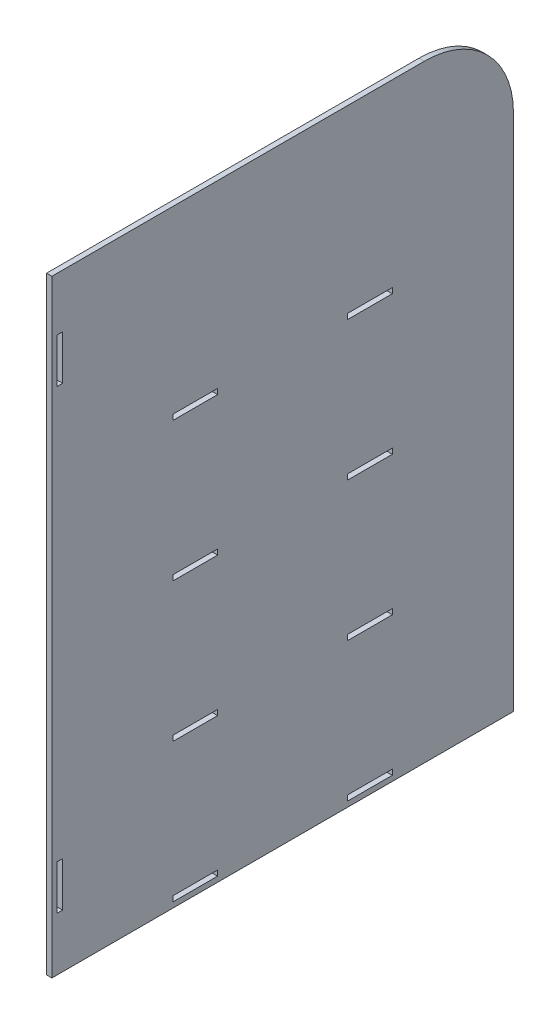
SolidWorks part; units mm, degrees
material "Maple"
ref_plane "Front Plane" through (0, 0, 0) normal (0, 0, 1) x (1, 0, 0)
ref_plane "Top Plane" through (0, 0, 0) normal (0, 1, 0) x (1, 0, 0)
ref_plane "Right Plane" through (0, 0, 0) normal (1, 0, 0) x (0, 0, -1)
sketch "Sketch1" plane through (0, 0, 0) normal (1, 0, 0) x (0, 0, -1)
  line L0 (-155.8318, 16.1512) -> (-414.8318, 16.1512) construction
  line L1 (-414.8318, 357.1512) -> (3.1682, 357.1512)
  line L2 (-414.8318, 357.1512) -> (-414.8318, -324.8488)
  line L3 (-414.8318, -324.8488) -> (103.1682, -324.8488)
  line L4 (103.1682, 257.1512) -> (103.1682, -324.8488)
  line L5 (-414.8318, 357.1512) -> (103.1682, -324.8488) construction
  line L6 (-414.8318, -324.8488) -> (103.1682, 357.1512) construction
  line L7 (-408.8318, 297.1512) -> (-402.8318, 297.1512)
  line L8 (-408.8318, 297.1512) -> (-408.8318, 247.1512)
  line L9 (-408.8318, 247.1512) -> (-402.8318, 247.1512)
  line L10 (-402.8318, 297.1512) -> (-402.8318, 247.1512)
  line L15 (-155.8318, 16.1512) -> (-155.8318, -324.8488) construction
  line L16 (-278.8318, -312.8488) -> (-228.8318, -312.8488)
  line L17 (-278.8318, -312.8488) -> (-278.8318, -318.8488)
  line L18 (-278.8318, -318.8488) -> (-228.8318, -318.8488)
  line L19 (-228.8318, -312.8488) -> (-228.8318, -318.8488)
  line L20 (-278.8318, -312.8488) -> (-228.8318, -318.8488) construction
  line L21 (-278.8318, -318.8488) -> (-228.8318, -312.8488) construction
  line L22 (-32.8318, -318.8488) -> (-82.8318, -318.8488)
  line L23 (-82.8318, -312.8488) -> (-82.8318, -318.8488)
  line L24 (-32.8318, -312.8488) -> (-82.8318, -312.8488)
  line L25 (-32.8318, -312.8488) -> (-32.8318, -318.8488)
  line L26 (-278.8318, -156.8488) -> (-278.8318, -162.8488)
  line L27 (-278.8318, -156.8488) -> (-228.8318, -156.8488)
  line L28 (-228.8318, -156.8488) -> (-228.8318, -162.8488)
  line L29 (-278.8318, -162.8488) -> (-228.8318, -162.8488)
  line L30 (-32.8318, -162.8488) -> (-82.8318, -162.8488)
  line L31 (-82.8318, -156.8488) -> (-82.8318, -162.8488)
  line L32 (-32.8318, -156.8488) -> (-82.8318, -156.8488)
  line L33 (-32.8318, -156.8488) -> (-32.8318, -162.8488)
  line L34 (-278.8318, -0.8488) -> (-278.8318, -6.8488)
  line L35 (-278.8318, -0.8488) -> (-228.8318, -0.8488)
  line L36 (-228.8318, -0.8488) -> (-228.8318, -6.8488)
  line L37 (-278.8318, -6.8488) -> (-228.8318, -6.8488)
  line L38 (-32.8318, -6.8488) -> (-82.8318, -6.8488)
  line L39 (-82.8318, -0.8488) -> (-82.8318, -6.8488)
  line L40 (-32.8318, -0.8488) -> (-82.8318, -0.8488)
  line L41 (-32.8318, -0.8488) -> (-32.8318, -6.8488)
  line L42 (-278.8318, 155.1512) -> (-278.8318, 149.1512)
  line L43 (-278.8318, 155.1512) -> (-228.8318, 155.1512)
  line L44 (-228.8318, 155.1512) -> (-228.8318, 149.1512)
  line L45 (-278.8318, 149.1512) -> (-228.8318, 149.1512)
  line L46 (-32.8318, 149.1512) -> (-82.8318, 149.1512)
  line L47 (-82.8318, 155.1512) -> (-82.8318, 149.1512)
  line L48 (-32.8318, 155.1512) -> (-82.8318, 155.1512)
  line L49 (-32.8318, 155.1512) -> (-32.8318, 149.1512)
  line L50 (-408.8318, -214.8488) -> (-402.8318, -214.8488)
  line L51 (-402.8318, -264.8488) -> (-402.8318, -214.8488)
  line L52 (-408.8318, -264.8488) -> (-402.8318, -264.8488)
  line L53 (-408.8318, -264.8488) -> (-408.8318, -214.8488)
  arc A0 (103.1682, 257.1512) -> (3.1682, 357.1512) centre (3.1682, 257.1512) ccw
  point P0 (-155.8318, 16.1512)
  point P18 (-253.8318, -315.8488)
  dimension "D3" = 100
  dimension "D1" = 682
  dimension "D2" = 518
  dimension "D4" = 60
  dimension "D5" = 6
  dimension "D6" = 6
  dimension "D7" = 50
  dimension "D8" = 150
  dimension "D9" = 136
  dimension "D11" = 6
  dimension "D13" = 136
  dimension "D14" = 136
  dimension "D15" = 6
  dimension "D16" = 150
  dimension "D12" = 4
extrude "Boss-Extrude1" add sketch "Sketch1" along normal blind 6
